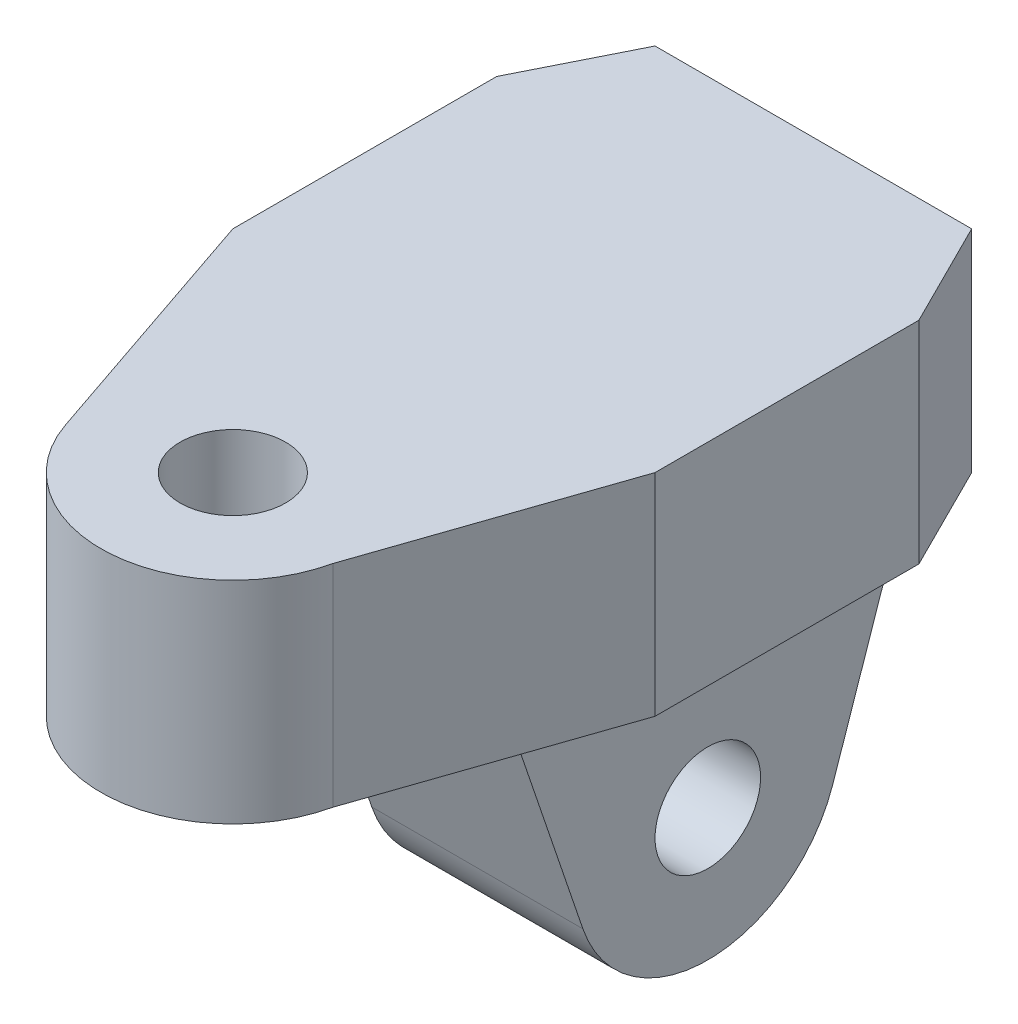
SolidWorks part; units mm, degrees
ref_plane "정면" through (0, 0, 0) normal (0, 0, 1) x (1, 0, 0)
ref_plane "윗면" through (0, 0, 0) normal (0, 1, 0) x (1, 0, 0)
ref_plane "우측면" through (0, 0, 0) normal (1, 0, 0) x (0, 0, -1)
sketch "스케치1" plane through (0, 0, 0) normal (1, 0, 0) x (0, 0, -1)
  line L0 (-12, 12) -> (12, 12)
  line L1 (12, 12) -> (7.101, -2.4135)
  line L2 (-12, 12) -> (-7.101, -2.4135)
  circle A0 centre (0, 0) radius 3
  arc A1 (-7.101, -2.4135) -> (7.101, -2.4135) centre (0, 0) ccw
  point P7 (0, 12)
  dimension "D1" = 6
  dimension "D2" = 15
  dimension "D3" = 24
  dimension "D4" = 12
extrude "보스-돌출1" add sketch "스케치1" along normal mid plane 12
sketch "스케치2" plane through (0, 12, 0) normal (0, 1, 0) x (1, 0, 0)
  line L0 (-12, -9) -> (12, -9)
  line L1 (12, -9) -> (7.3192, -22.6371)
  line L2 (-12, -9) -> (-7.101, -23.4135)
  circle A0 centre (0, -21) radius 3
  arc A1 (-7.101, -23.4135) -> (7.3192, -22.6371) centre (0, -21) ccw
  point P5 (0, -9)
  dimension "D3" = 6
  dimension "D4" = 15
  dimension "D1" = 24
  dimension "D2" = 12
  dimension "D5" = 9
extrude "보스-돌출2" add sketch "스케치2" along normal blind 12
sketch "스케치3" plane through (0, 0, 9) normal (0, 0, -1) x (-1, 0, 0)
  line L6 (-12, 12) -> (-6, 12)
  line L7 (-6, 12) -> (6, 12)
  line L8 (6, 12) -> (12, 12)
  line L9 (12, 12) -> (12, 24)
  line L10 (12, 24) -> (-12, 24)
  line L11 (-12, 24) -> (-12, 12)
  line L12 (-12, 12) -> (-6, 12)
  line L13 (-6, 12) -> (6, 12)
  line L14 (6, 12) -> (12, 12)
  line L15 (12, 12) -> (12, 24)
  line L16 (12, 24) -> (-12, 24)
  line L17 (-12, 24) -> (-12, 12)
  dimension "D1" = 0
extrude "보스-돌출3" add sketch "스케치3" along normal blind 3
sketch "스케치4" plane through (0, 0, 6) normal (0, 0, -1) x (-1, 0, 0)
  line L0 (-9, 12) -> (-6, 9)
  line L1 (-6, -2.4135) -> (-6, 12) construction
  line L2 (9, 12) -> (6, 9)
  line L3 (6, -2.4135) -> (6, 12) construction
  line L4 (-6, 9) -> (-6, 12)
  line L5 (6, 9) -> (6, 12)
  line L6 (-12, 24) -> (-12, 12)
  line L7 (-12, 12) -> (-6, 12)
  line L8 (-6, 12) -> (6, 12)
  line L9 (6, 12) -> (12, 12)
  line L10 (12, 12) -> (12, 24)
  line L11 (12, 24) -> (-12, 24)
  line L12 (-12, 24) -> (-12, 12)
  line L13 (-12, 12) -> (-9, 12)
  line L14 (-6, 12) -> (6, 12)
  line L15 (9, 12) -> (12, 12)
  line L16 (12, 12) -> (12, 24)
  line L17 (12, 24) -> (-12, 24)
  dimension "D2" = 3
  dimension "D3" = 3
  dimension "D4" = 3
  dimension "D5" = 3
  dimension "D1" = 0
extrude "보스-돌출4" add sketch "스케치4" along normal blind 12
sketch "스케치5" plane through (0, 12, 0) normal (0, 1, 0) x (1, 0, 0)
  line L0 (-12, 6) -> (12, 6)
  line L1 (12, 6) -> (9, 12)
  line L2 (9, 12) -> (-9, 12)
  line L3 (-9, 12) -> (-12, 6)
  dimension "D1" = 3
  dimension "D2" = 3
extrude "보스-돌출5" add sketch "스케치5" along normal blind 12
